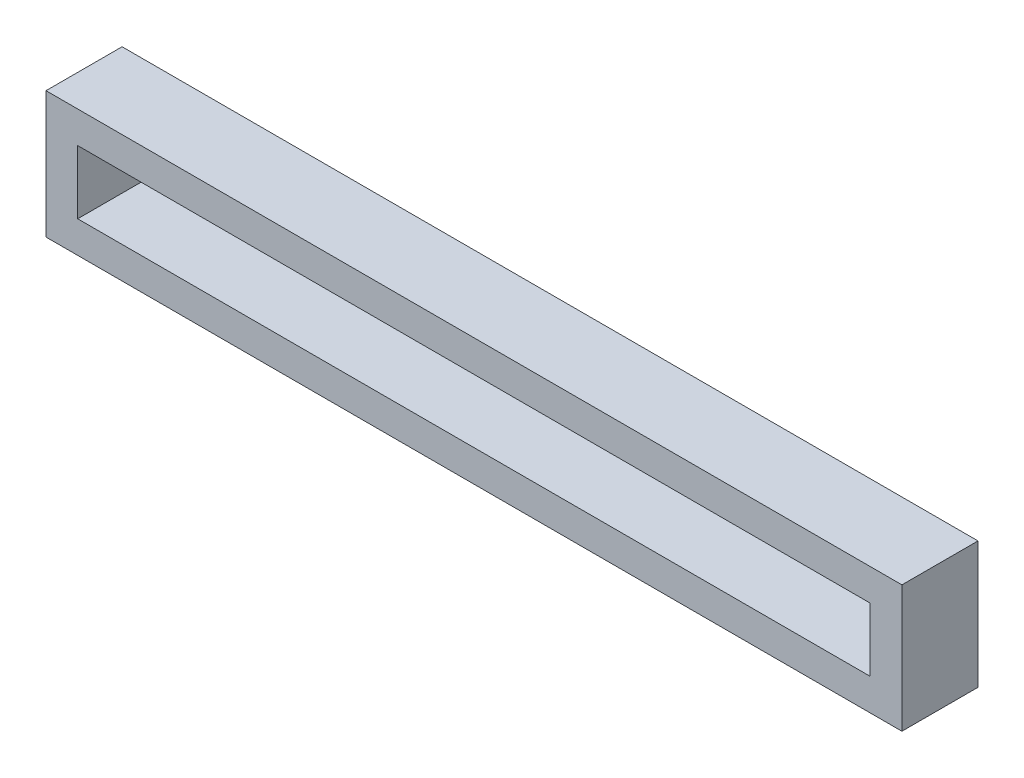
SolidWorks part; units mm, degrees
ref_plane "Alzado" through (0, 0, 0) normal (0, 0, 1) x (1, 0, 0)
ref_plane "Planta" through (0, 0, 0) normal (0, 1, 0) x (1, 0, 0)
ref_plane "Vista lateral" through (0, 0, 0) normal (1, 0, 0) x (0, 0, -1)
sketch "Croquis1" plane through (0, 0, 0) normal (0, 0, 1) x (1, 0, 0)
  line L0 (0, 0) -> (125, 0)
  line L1 (125, 0) -> (125, 10)
  line L2 (125, 10) -> (0, 10)
  line L3 (0, 10) -> (0, 0)
  line L4 (-5, 15) -> (-5, -5)
  line L5 (-5, -5) -> (130, -5)
  line L6 (130, -5) -> (130, 15)
  line L7 (130, 15) -> (-5, 15)
  dimension "D1" = 125
  dimension "D2" = 10
  dimension "D3" = 5
extrude "Saliente-Extruir1" add sketch "Croquis1" along normal blind 10
sketch "Croquis2" plane through (0, 0, 0) normal (0, 0, -1) x (-1, 0, 0)
  line L1 (-130, 15) -> (5, 15)
  line L2 (-130, 15) -> (-130, -5)
  line L3 (-130, -5) -> (5, -5)
  line L4 (5, 15) -> (5, -5)
extrude "Saliente-Extruir2" add sketch "Croquis2" along normal blind 2
